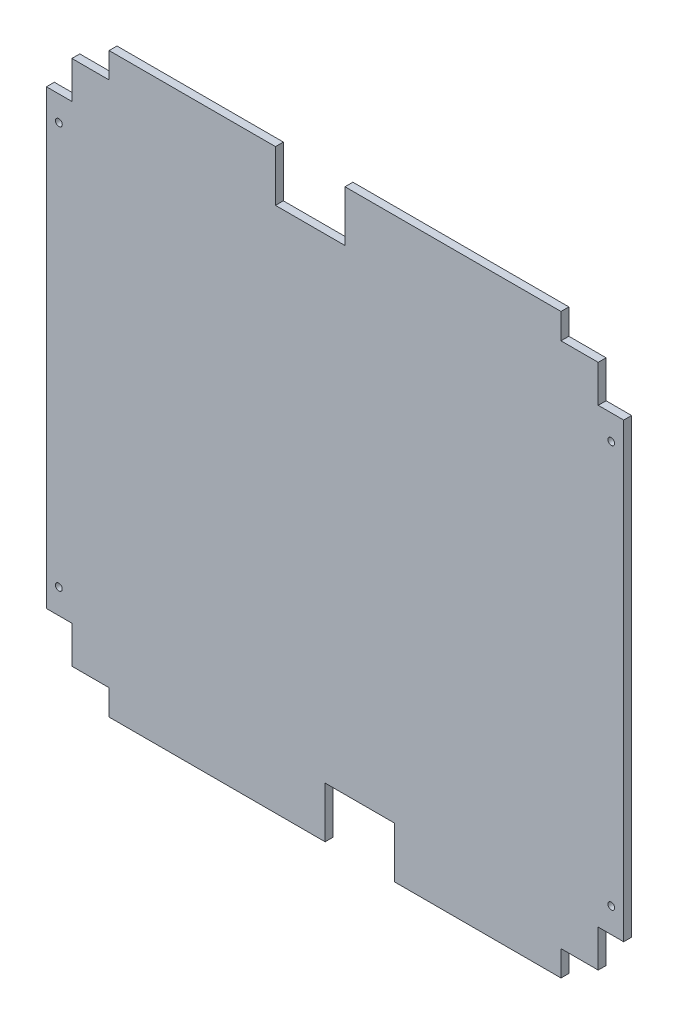
SolidWorks part; units mm, degrees
material "Acrylic (Medium-high impact)"
ref_plane "Front Plane" through (0, 0, 0) normal (0, 0, 1) x (1, 0, 0)
ref_plane "Top Plane" through (0, 0, 0) normal (0, 1, 0) x (1, 0, 0)
ref_plane "Right Plane" through (0, 0, 0) normal (1, 0, 0) x (0, 0, -1)
sketch "Sketch1" plane through (0, 0, 0) normal (0, 0, 1) x (1, 0, 0)
  line L0 (182, -212) -> (212, -212)
  line L1 (-182, -232.5) -> (-8, -232.5)
  line L2 (-232.5, -182) -> (-232.5, 0)
  line L3 (212, -212) -> (212, -182)
  line L4 (232.5, -182) -> (232.5, 0)
  line L5 (48, -232.5) -> (182, -232.5)
  line L6 (-232.5, 0) -> (232.5, 0) construction
  line L7 (-182, -212) -> (-212, -212)
  line L8 (-212, -212) -> (-212, -182)
  line L9 (232.5, 182) -> (232.5, 0)
  line L10 (232.5, 182) -> (212, 182)
  line L11 (212, 212) -> (212, 182)
  line L12 (182, 212) -> (212, 212)
  line L13 (182, 232.5) -> (182, 212)
  line L14 (182, 232.5) -> (8, 232.5)
  line L15 (8, 232.5) -> (8, 191.5)
  line L16 (-48, 191.5) -> (8, 191.5)
  line L17 (-48, 232.5) -> (-48, 191.5)
  line L18 (-48, 232.5) -> (-182, 232.5)
  line L19 (-182, 232.5) -> (-182, 212)
  line L20 (-182, 212) -> (-212, 212)
  line L21 (232.5, -182) -> (212, -182)
  line L22 (182, -232.5) -> (182, -212)
  line L23 (-212, 212) -> (-212, 182)
  line L24 (48, -232.5) -> (48, -191.5)
  line L25 (48, -191.5) -> (-8, -191.5)
  line L26 (-8, -232.5) -> (-8, -191.5)
  line L27 (-232.5, 182) -> (-212, 182)
  line L28 (-232.5, 182) -> (-232.5, 0)
  line L29 (-232.5, -182) -> (-212, -182)
  line L30 (-182, -232.5) -> (-182, -212)
  line L31 (0, 0) -> (0, -232.5) construction
  circle A0 centre (-222.5, -162) radius 2.75
  circle A1 centre (222.5, -162) radius 2.75
  circle A2 centre (222.5, 162) radius 2.75
  circle A3 centre (-222.5, 162) radius 2.75
  point P0 (0, 0)
  point P3 (0, 0)
  point P38 (0, 0)
  point P40 (20, -191.5)
  point P68 (0, 0)
  dimension "D21" = 20.5
  dimension "D22" = 20.5
  dimension "D23" = 232.5
  dimension "D7" = 5.5
  dimension "D8" = 10
  dimension "D9" = 20
  dimension "D3" = 50.5
  dimension "D4" = 20.5
  dimension "D5" = 20.5
  dimension "D6" = 2
  dimension "D10" = 20
  dimension "D11" = 50.5
  dimension "D12" = 50.5
  dimension "D15" = 56
  dimension "D16" = 41
  dimension "D18" = 50.5
  dimension "D20" = 465
extrude "Boss-Extrude1" add sketch "Sketch1" along normal blind 6.35
